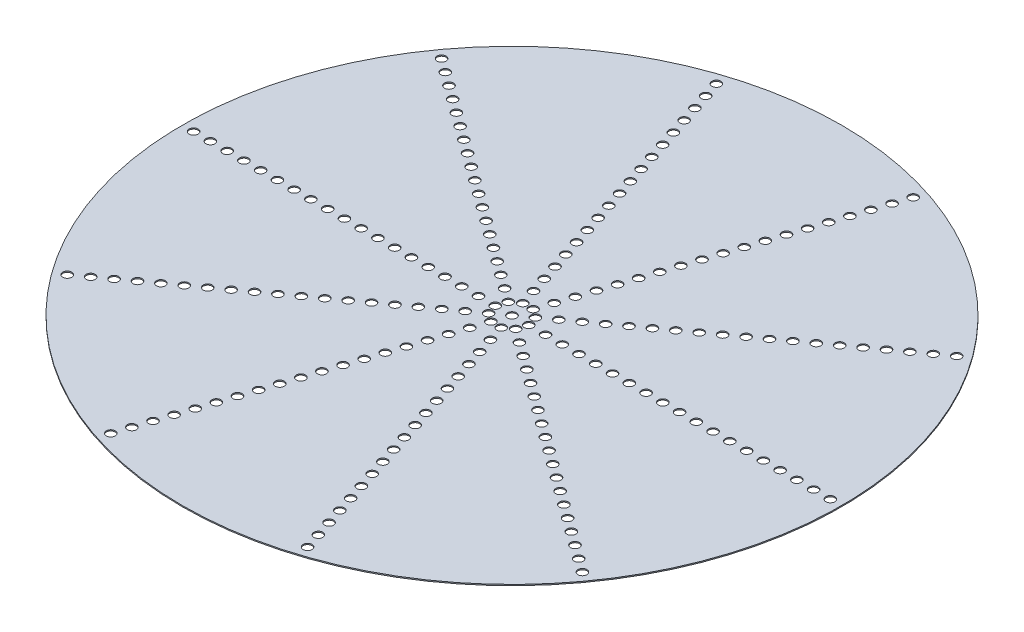
SolidWorks part; units mm, degrees
material "1060 Alloy"
ref_plane "Front Plane" through (0, 0, 0) normal (0, 0, 1) x (1, 0, 0)
ref_plane "Top Plane" through (0, 0, 0) normal (0, 1, 0) x (1, 0, 0)
ref_plane "Right Plane" through (0, 0, 0) normal (1, 0, 0) x (0, 0, -1)
sketch "Croquis1" plane through (0, 0, 0) normal (0, 1, 0) x (1, 0, 0)
  circle A0 centre (0, 0) radius 29.5
  dimension "D1" = 59
extrude "Saliente-Extruir1" add sketch "Croquis1" along normal blind 0.1
sketch "Croquis3" plane through (0, 0.1, 0) normal (0, 1, 0) x (1, 0, 0)
  circle A0 centre (0, 0) radius 0.4
  circle A1 centre (1.5, 0) radius 0.4
  circle A2 centre (3, 0) radius 0.4
  circle A3 centre (4.5, 0) radius 0.4
  circle A4 centre (6, 0) radius 0.4
  circle A5 centre (7.5, 0) radius 0.4
  circle A6 centre (9, 0) radius 0.4
  circle A7 centre (10.5, 0) radius 0.4
  circle A8 centre (12, 0) radius 0.4
  circle A9 centre (13.5, 0) radius 0.4
  circle A10 centre (15, 0) radius 0.4
  circle A11 centre (16.5, 0) radius 0.4
  circle A12 centre (18, 0) radius 0.4
  circle A13 centre (19.5, 0) radius 0.4
  circle A14 centre (21, 0) radius 0.4
  circle A15 centre (22.5, 0) radius 0.4
  circle A16 centre (24, 0) radius 0.4
  circle A17 centre (25.5, 0) radius 0.4
  circle A18 centre (27, 0) radius 0.4
  circle A19 centre (28.5, 0) radius 0.4
  circle A20 centre (14.5623, -10.5801) radius 0.4
  circle A21 centre (13.3488, -9.6985) radius 0.4
  circle A22 centre (12.1353, -8.8168) radius 0.4
  circle A23 centre (10.9217, -7.9351) radius 0.4
  circle A24 centre (9.7082, -7.0534) radius 0.4
  circle A25 centre (8.4947, -6.1717) radius 0.4
  circle A26 centre (7.2812, -5.2901) radius 0.4
  circle A27 centre (6.0676, -4.4084) radius 0.4
  circle A28 centre (4.8541, -3.5267) radius 0.4
  circle A29 centre (2.4271, -1.7634) radius 0.4
  circle A30 centre (1.2135, -0.8817) radius 0.4
  circle A31 centre (3.6406, -2.645) radius 0.4
  circle A32 centre (15.7758, -11.4618) radius 0.4
  circle A33 centre (16.9894, -12.3435) radius 0.4
  circle A34 centre (18.2029, -13.2252) radius 0.4
  circle A35 centre (19.4164, -14.1068) radius 0.4
  circle A36 centre (20.6299, -14.9885) radius 0.4
  circle A37 centre (21.8435, -15.8702) radius 0.4
  circle A38 centre (23.057, -16.7519) radius 0.4
  circle A39 centre (5.5623, -17.119) radius 0.4
  circle A40 centre (5.0988, -15.6924) radius 0.4
  circle A41 centre (4.6353, -14.2658) radius 0.4
  circle A42 centre (4.1717, -12.8393) radius 0.4
  circle A43 centre (3.7082, -11.4127) radius 0.4
  circle A44 centre (3.2447, -9.9861) radius 0.4
  circle A45 centre (2.7812, -8.5595) radius 0.4
  circle A46 centre (2.3176, -7.1329) radius 0.4
  circle A47 centre (1.8541, -5.7063) radius 0.4
  circle A48 centre (0.9271, -2.8532) radius 0.4
  circle A49 centre (0.4635, -1.4266) radius 0.4
  circle A50 centre (1.3906, -4.2798) radius 0.4
  circle A51 centre (6.0258, -18.5456) radius 0.4
  circle A52 centre (6.4894, -19.9722) radius 0.4
  circle A53 centre (6.9529, -21.3988) radius 0.4
  circle A54 centre (7.4164, -22.8254) radius 0.4
  circle A55 centre (7.8799, -24.2519) radius 0.4
  circle A56 centre (8.3435, -25.6785) radius 0.4
  circle A57 centre (8.807, -27.1051) radius 0.4
  circle A58 centre (-5.5623, -17.119) radius 0.4
  circle A59 centre (-5.0988, -15.6924) radius 0.4
  circle A60 centre (-4.6353, -14.2658) radius 0.4
  circle A61 centre (-4.1717, -12.8393) radius 0.4
  circle A62 centre (-3.7082, -11.4127) radius 0.4
  circle A63 centre (-3.2447, -9.9861) radius 0.4
  circle A64 centre (-2.7812, -8.5595) radius 0.4
  circle A65 centre (-2.3176, -7.1329) radius 0.4
  circle A66 centre (-1.8541, -5.7063) radius 0.4
  circle A67 centre (-0.9271, -2.8532) radius 0.4
  circle A68 centre (-0.4635, -1.4266) radius 0.4
  circle A69 centre (-1.3906, -4.2798) radius 0.4
  circle A70 centre (-6.0258, -18.5456) radius 0.4
  circle A71 centre (-6.4894, -19.9722) radius 0.4
  circle A72 centre (-6.9529, -21.3988) radius 0.4
  circle A73 centre (-7.4164, -22.8254) radius 0.4
  circle A74 centre (-7.8799, -24.2519) radius 0.4
  circle A75 centre (-8.3435, -25.6785) radius 0.4
  circle A76 centre (-8.807, -27.1051) radius 0.4
  circle A77 centre (-14.5623, -10.5801) radius 0.4
  circle A78 centre (-13.3488, -9.6985) radius 0.4
  circle A79 centre (-12.1353, -8.8168) radius 0.4
  circle A80 centre (-10.9217, -7.9351) radius 0.4
  circle A81 centre (-9.7082, -7.0534) radius 0.4
  circle A82 centre (-8.4947, -6.1717) radius 0.4
  circle A83 centre (-7.2812, -5.2901) radius 0.4
  circle A84 centre (-6.0676, -4.4084) radius 0.4
  circle A85 centre (-4.8541, -3.5267) radius 0.4
  circle A86 centre (-2.4271, -1.7634) radius 0.4
  circle A87 centre (-1.2135, -0.8817) radius 0.4
  circle A88 centre (-3.6406, -2.645) radius 0.4
  circle A89 centre (-15.7758, -11.4618) radius 0.4
  circle A90 centre (-16.9894, -12.3435) radius 0.4
  circle A91 centre (-18.2029, -13.2252) radius 0.4
  circle A92 centre (-19.4164, -14.1068) radius 0.4
  circle A93 centre (-20.6299, -14.9885) radius 0.4
  circle A94 centre (-21.8435, -15.8702) radius 0.4
  circle A95 centre (-23.057, -16.7519) radius 0.4
  circle A96 centre (-18, 0) radius 0.4
  circle A97 centre (-16.5, 0) radius 0.4
  circle A98 centre (-15, 0) radius 0.4
  circle A99 centre (-13.5, 0) radius 0.4
  circle A100 centre (-12, 0) radius 0.4
  circle A101 centre (-10.5, 0) radius 0.4
  circle A102 centre (-9, 0) radius 0.4
  circle A103 centre (-7.5, 0) radius 0.4
  circle A104 centre (-6, 0) radius 0.4
  circle A105 centre (-3, 0) radius 0.4
  circle A106 centre (-1.5, 0) radius 0.4
  circle A107 centre (-4.5, 0) radius 0.4
  circle A108 centre (-19.5, 0) radius 0.4
  circle A109 centre (-21, 0) radius 0.4
  circle A110 centre (-22.5, 0) radius 0.4
  circle A111 centre (-24, 0) radius 0.4
  circle A112 centre (-25.5, 0) radius 0.4
  circle A113 centre (-27, 0) radius 0.4
  circle A114 centre (-28.5, 0) radius 0.4
  circle A115 centre (-14.5623, 10.5801) radius 0.4
  circle A116 centre (-13.3488, 9.6985) radius 0.4
  circle A117 centre (-12.1353, 8.8168) radius 0.4
  circle A118 centre (-10.9217, 7.9351) radius 0.4
  circle A119 centre (-9.7082, 7.0534) radius 0.4
  circle A120 centre (-8.4947, 6.1717) radius 0.4
  circle A121 centre (-7.2812, 5.2901) radius 0.4
  circle A122 centre (-6.0676, 4.4084) radius 0.4
  circle A123 centre (-4.8541, 3.5267) radius 0.4
  circle A124 centre (-2.4271, 1.7634) radius 0.4
  circle A125 centre (-1.2135, 0.8817) radius 0.4
  circle A126 centre (-3.6406, 2.645) radius 0.4
  circle A127 centre (-15.7758, 11.4618) radius 0.4
  circle A128 centre (-16.9894, 12.3435) radius 0.4
  circle A129 centre (-18.2029, 13.2252) radius 0.4
  circle A130 centre (-19.4164, 14.1068) radius 0.4
  circle A131 centre (-20.6299, 14.9885) radius 0.4
  circle A132 centre (-21.8435, 15.8702) radius 0.4
  circle A133 centre (-23.057, 16.7519) radius 0.4
  circle A134 centre (-5.5623, 17.119) radius 0.4
  circle A135 centre (-5.0988, 15.6924) radius 0.4
  circle A136 centre (-4.6353, 14.2658) radius 0.4
  circle A137 centre (-4.1717, 12.8393) radius 0.4
  circle A138 centre (-3.7082, 11.4127) radius 0.4
  circle A139 centre (-3.2447, 9.9861) radius 0.4
  circle A140 centre (-2.7812, 8.5595) radius 0.4
  circle A141 centre (-2.3176, 7.1329) radius 0.4
  circle A142 centre (-1.8541, 5.7063) radius 0.4
  circle A143 centre (-0.9271, 2.8532) radius 0.4
  circle A144 centre (-0.4635, 1.4266) radius 0.4
  circle A145 centre (-1.3906, 4.2798) radius 0.4
  circle A146 centre (-6.0258, 18.5456) radius 0.4
  circle A147 centre (-6.4894, 19.9722) radius 0.4
  circle A148 centre (-6.9529, 21.3988) radius 0.4
  circle A149 centre (-7.4164, 22.8254) radius 0.4
  circle A150 centre (-7.8799, 24.2519) radius 0.4
  circle A151 centre (-8.3435, 25.6785) radius 0.4
  circle A152 centre (-8.807, 27.1051) radius 0.4
  circle A153 centre (5.5623, 17.119) radius 0.4
  circle A154 centre (5.0988, 15.6924) radius 0.4
  circle A155 centre (4.6353, 14.2658) radius 0.4
  circle A156 centre (4.1717, 12.8393) radius 0.4
  circle A157 centre (3.7082, 11.4127) radius 0.4
  circle A158 centre (3.2447, 9.9861) radius 0.4
  circle A159 centre (2.7812, 8.5595) radius 0.4
  circle A160 centre (2.3176, 7.1329) radius 0.4
  circle A161 centre (1.8541, 5.7063) radius 0.4
  circle A162 centre (0.9271, 2.8532) radius 0.4
  circle A163 centre (0.4635, 1.4266) radius 0.4
  circle A164 centre (1.3906, 4.2798) radius 0.4
  circle A165 centre (6.0258, 18.5456) radius 0.4
  circle A166 centre (6.4894, 19.9722) radius 0.4
  circle A167 centre (6.9529, 21.3988) radius 0.4
  circle A168 centre (7.4164, 22.8254) radius 0.4
  circle A169 centre (7.8799, 24.2519) radius 0.4
  circle A170 centre (8.3435, 25.6785) radius 0.4
  circle A171 centre (8.807, 27.1051) radius 0.4
  circle A172 centre (14.5623, 10.5801) radius 0.4
  circle A173 centre (13.3488, 9.6985) radius 0.4
  circle A174 centre (12.1353, 8.8168) radius 0.4
  circle A175 centre (10.9217, 7.9351) radius 0.4
  circle A176 centre (9.7082, 7.0534) radius 0.4
  circle A177 centre (8.4947, 6.1717) radius 0.4
  circle A178 centre (7.2812, 5.2901) radius 0.4
  circle A179 centre (6.0676, 4.4084) radius 0.4
  circle A180 centre (4.8541, 3.5267) radius 0.4
  circle A181 centre (2.4271, 1.7634) radius 0.4
  circle A182 centre (1.2135, 0.8817) radius 0.4
  circle A183 centre (3.6406, 2.645) radius 0.4
  circle A184 centre (15.7758, 11.4618) radius 0.4
  circle A185 centre (16.9894, 12.3435) radius 0.4
  circle A186 centre (18.2029, 13.2252) radius 0.4
  circle A187 centre (19.4164, 14.1068) radius 0.4
  circle A188 centre (20.6299, 14.9885) radius 0.4
  circle A189 centre (21.8435, 15.8702) radius 0.4
  circle A190 centre (23.057, 16.7519) radius 0.4
  point P386 (0, 0)
  dimension "D1" = 0.8
  dimension "D2" = 20
  dimension "D3" = 10
extrude "Cortar-Extruir3" cut sketch "Croquis3" against normal through all
